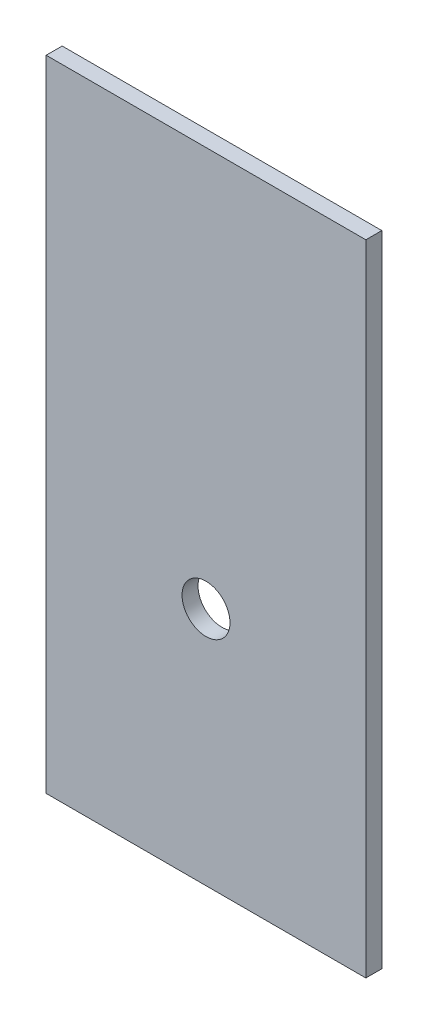
SolidWorks part; units mm, degrees
ref_plane "Alzado" through (0, 0, 0) normal (0, 0, 1) x (1, 0, 0)
ref_plane "Planta" through (0, 0, 0) normal (0, 1, 0) x (1, 0, 0)
ref_plane "Vista lateral" through (0, 0, 0) normal (1, 0, 0) x (0, 0, -1)
sketch "Croquis1" plane through (0, 0, 0) normal (0, 0, 1) x (1, 0, 0)
  line L1 (-100, -200) -> (100, -200)
  line L2 (-100, -200) -> (-100, 200)
  line L3 (-100, 200) -> (100, 200)
  line L4 (100, -200) -> (100, 200)
  line L5 (-100, -200) -> (100, 200) construction
  line L6 (-100, 200) -> (100, -200) construction
  circle A0 centre (0, -50) radius 15
  point P0 (0, 0)
  dimension "D3" = 250
  dimension "D4" = 30
  dimension "D1" = 200
  dimension "D2" = 400
extrude "Saliente-Extruir1" add sketch "Croquis1" along normal blind 10
